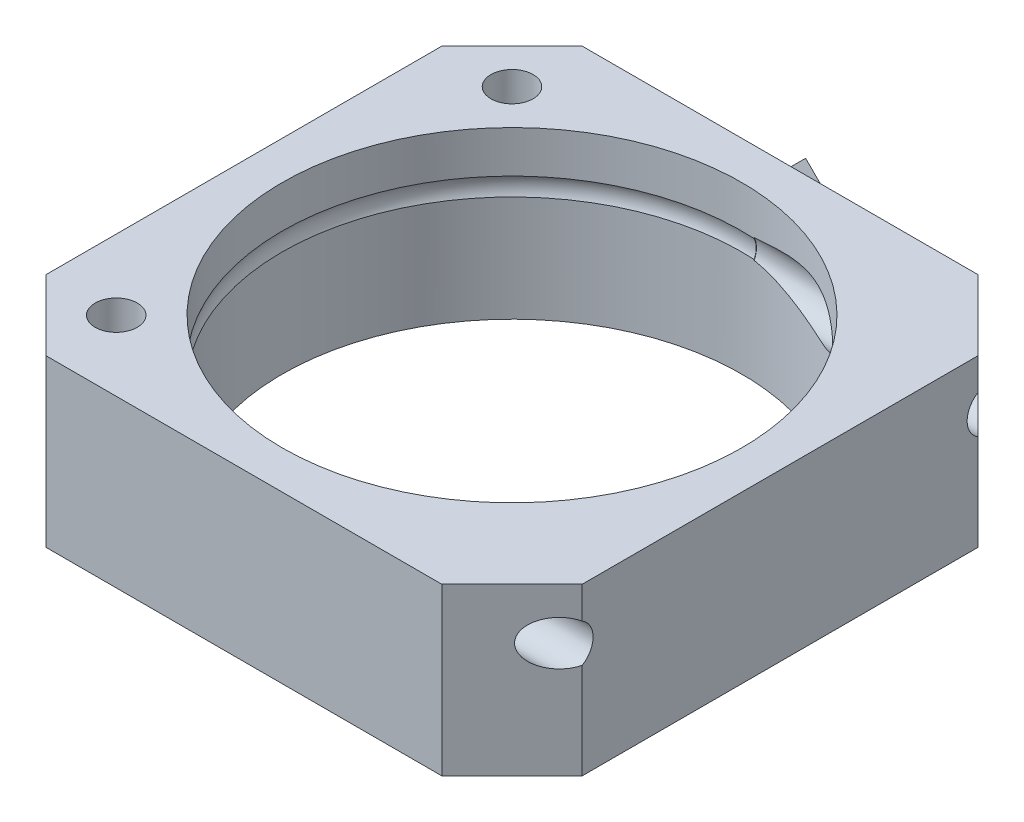
SolidWorks part; units mm, degrees
material "ABS"
ref_plane "Front Plane" through (0, 0, 0) normal (0, 0, 1) x (1, 0, 0)
ref_plane "Top Plane" through (0, 0, 0) normal (0, 1, 0) x (1, 0, 0)
ref_plane "Right Plane" through (0, 0, 0) normal (1, 0, 0) x (0, 0, -1)
sketch "Sketch1" plane through (0, 0, 0) normal (0, 1, 0) x (1, 0, 0)
  line L1 (0, 0) -> (42, 0)
  line L2 (0, 0) -> (0, 42)
  line L3 (0, 42) -> (42, 42)
  line L4 (42, 0) -> (42, 42)
  circle A0 centre (5.5, 36.5) radius 1.65
  circle A1 centre (5.5, 5.5) radius 1.65
  circle A4 centre (21, 21) radius 18
  point P16 (21, 21)
  dimension "D3" = 5.5
  dimension "D5" = 3.3
  dimension "D7" = 36
  dimension "D6" = 5.5
  dimension "D9" = 3.3
  dimension "D1" = 42
  dimension "D2" = 42
  dimension "D4" = 5.5
  dimension "D8" = 5.5
extrude "Boss-Extrude1" add sketch "Sketch1" along normal blind 13
chamfer "Chamfer1" distance 5.5 angle 45 4 edges at (42, 6.5, 0) (42, 6.5, -42) (0, 6.5, 0) (0, 6.5, -42)
sketch "Sketch3" plane through (42, 0, 0) normal (1, 0, 0) x (0, 0, -1)
  line L0 (5.5, 0) -> (36.5, 0) construction
  line L1 (42, 13) -> (42, 0) construction
  circle A0 centre (37.4, 9) radius 1.75
  dimension "D1" = 9
  dimension "D2" = 3.5
  dimension "D3" = 4.6
extrude "Cut-Extrude2" cut sketch "Sketch3" against normal blind 20
sketch "Sketch4" plane through (42, 0, 0) normal (1, 0, 0) x (0, 0, -1)
  line L0 (5.5, 0) -> (36.5, 0) construction
  line L1 (0, 0) -> (0, 13) construction
  circle A0 centre (4.6, 9) radius 1.75
  dimension "D1" = 9
  dimension "D3" = 3.5
  dimension "D2" = 4.6
extrude "Cut-Extrude3" cut sketch "Sketch4" against normal blind 20
sketch "Sketch6" plane through (0, 0, -42) normal (0, 0, -1) x (-1, 0, 0)
  line L0 (-23.4684, 0.8296) -> (-18.5316, 0.8296)
  line L1 (-18.5316, 0.8296) -> (-18.5316, 5.9449)
  line L2 (-18.5316, 5.9449) -> (-14.8, 5.9449)
  line L3 (-14.8, 5.9449) -> (-21, 12.1449)
  line L4 (-21, 12.1449) -> (-27.2, 5.9449)
  line L5 (-27.2, 5.9449) -> (-23.4684, 5.9449)
  line L6 (-23.4684, 5.9449) -> (-23.4684, 0.8296)
  line L9 (-36.5, 13) -> (-36.5, 0) construction
  line L10 (-5.5, 0) -> (-5.5, 13) construction
  dimension "D1" = 3.7316
  dimension "D2" = 9.3
  dimension "D3" = 9.3
extrude "Boss-Extrude2" add sketch "Sketch6" along normal blind 2
ref_plane "Plane2" through (21, 0, 0) normal (1, 0, 0) x (0, 0, -1)
sketch "Sketch9" plane through (21, 0, 0) normal (1, 0, 0) x (0, 0, -1)
  line L0 (21, 18.1922) -> (21, -1.3214)
  line L2 (0, 0) -> (0, 13) construction
  line L3 (3.0278, 9.7686) -> (3.0278, 8.2314)
  arc A0 (3.0278, 9.7686) -> (3.0278, 8.2314) centre (4.6, 9) ccw
  point P3 (21, 8.4354)
  dimension "D1" = 21
revolve "Cut-Revolve1" cut sketch "Sketch9" angle 183.3 about L0 other way angle 3.2
